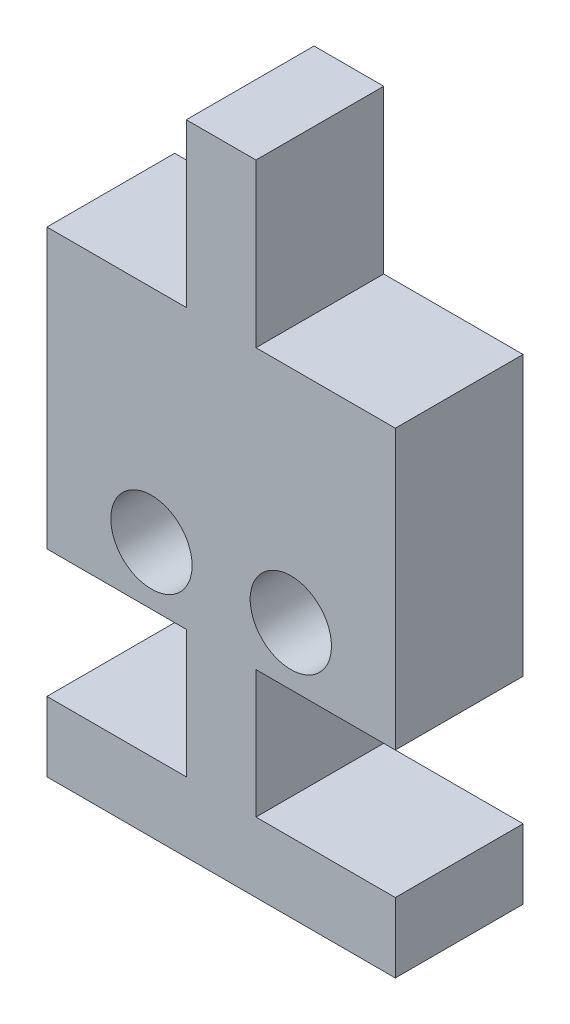
SolidWorks part; units mm, degrees
material "ﾁｰｸ材"
ref_plane "正面" through (0, 0, 0) normal (0, 0, 1) x (1, 0, 0)
ref_plane "平面" through (0, 0, 0) normal (0, 1, 0) x (1, 0, 0)
ref_plane "右側面" through (0, 0, 0) normal (1, 0, 0) x (0, 0, -1)
sketch "ｽｹｯﾁ1" plane through (0, 0, 0) normal (0, 0, 1) x (1, 0, 0)
  line L0 (1.5, -7) -> (7.5, -7)
  line L3 (1.5, 0) -> (-1.5, 0)
  line L7 (-7.5, -7) -> (-1.5, -7)
  line L8 (-7.5, -7) -> (-7.5, -19)
  line L9 (-7.5, -19) -> (-1.5, -19)
  line L10 (7.5, -7) -> (7.5, -19)
  line L11 (-7.5, -7) -> (7.5, -19) construction
  line L12 (-7.5, -19) -> (7.5, -7) construction
  line L13 (-7.5, -24.5) -> (-1.5, -24.5)
  line L14 (-7.5, -24.5) -> (-7.5, -27.5)
  line L15 (-7.5, -27.5) -> (7.5, -27.5)
  line L16 (7.5, -24.5) -> (7.5, -27.5)
  line L17 (-7.5, -24.5) -> (7.5, -27.5) construction
  line L18 (-7.5, -27.5) -> (7.5, -24.5) construction
  line L19 (-1.5, -7) -> (-1.5, 0)
  line L20 (1.5, -7) -> (1.5, 0)
  line L21 (1.5, -19) -> (7.5, -19)
  line L22 (-1.5, -24.5) -> (-1.5, -19)
  line L23 (1.5, -24.5) -> (7.5, -24.5)
  line L24 (1.5, -24.5) -> (1.5, -19)
  point P5 (0, -13)
  point P10 (0, -26)
  dimension "D1" = 19
  dimension "D2" = 5.5
  dimension "D3" = 3
  dimension "D4" = 12
  dimension "D5" = 3
  dimension "D6" = 15
  dimension "D7" = 15
extrude "ﾎﾞｽ - 押し出し1" add sketch "ｽｹｯﾁ1" along normal blind 5.5
sketch "ｽｹｯﾁ2" plane through (0, 0, 5.5) normal (0, 0, 1) x (1, 0, 0)
  line L0 (-7.5, -27.5) -> (7.5, -27.5) construction
  circle A0 centre (-3, -16.5) radius 1.75
  circle A1 centre (3, -16.5) radius 1.75
  dimension "D1" = 3.5
  dimension "D2" = 3
  dimension "D3" = 3
  dimension "D4" = 11
extrude "ｶｯﾄ - 押し出し1" cut sketch "ｽｹｯﾁ2" against normal through all
